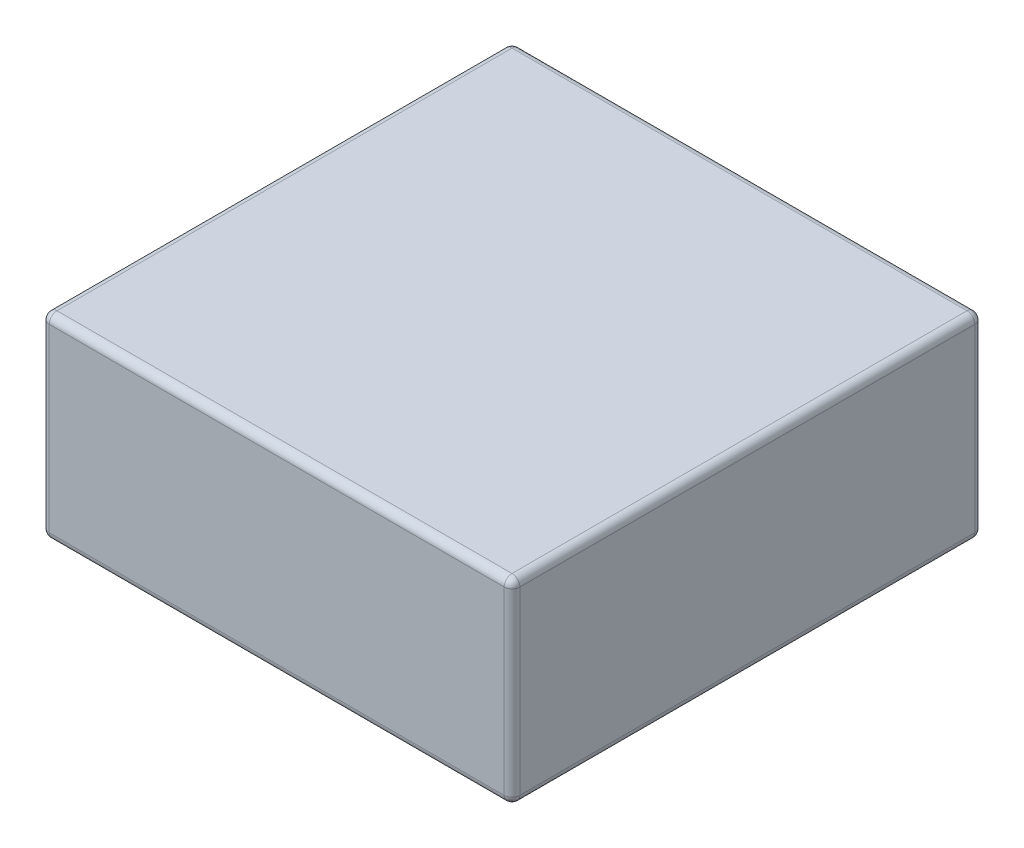
SolidWorks part; units mm, degrees
ref_plane "Front Plane" through (0, 0, 0) normal (0, 0, 1) x (1, 0, 0)
ref_plane "Top Plane" through (0, 0, 0) normal (0, 1, 0) x (1, 0, 0)
ref_plane "Right Plane" through (0, 0, 0) normal (1, 0, 0) x (0, 0, -1)
sketch "Sketch1" plane through (0, 0, 0) normal (1, 0, 0) x (0, 0, -1)
  line L1 (-30, 12.5) -> (30, 12.5)
  line L2 (-30, 12.5) -> (-30, -12.5)
  line L3 (-30, -12.5) -> (30, -12.5)
  line L4 (30, 12.5) -> (30, -12.5)
  line L5 (-30, 12.5) -> (30, -12.5) construction
  line L6 (-30, -12.5) -> (30, 12.5) construction
  point P0 (0, 0)
  dimension "D1" = 25
  dimension "D2" = 60
extrude "Boss-Extrude1" add sketch "Sketch1" against normal blind 60
fillet "Fillet1" radius 1 4 edges at (-60, 12.5, 0) (-60, -12.5, 0) (0, -12.5, 0) (0, 12.5, 0)
fillet "Fillet2" radius 1 16 edges at (-59.7071, 12.2071, -30) (-60, 0, -30) (-59.7071, -12.2071, -30) (-30, -12.5, -30) (-0.2929, -12.2071, -30) (0, 0, -30) (-0.2929, 12.2071, -30) (-59.7071, 12.2071, 30) (-60, 0, 30) (-59.7071, -12.2071, 30) (-30, -12.5, 30) (-0.2929, -12.2071, 30) (0, 0, 30) (-0.2929, 12.2071, 30) (-30, 12.5, -30) (-30, 12.5, 30)
